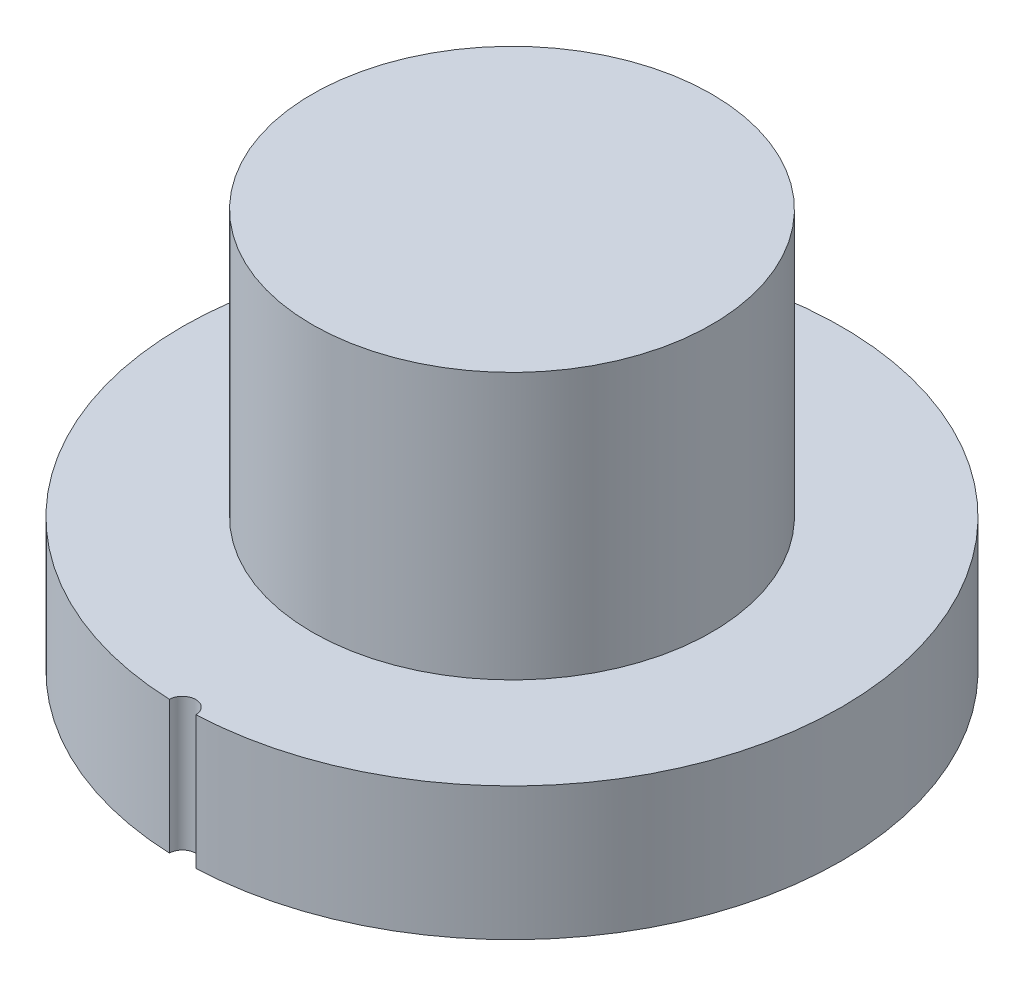
SolidWorks part; units mm, degrees
ref_plane "Front Plane" through (0, 0, 0) normal (0, 0, 1) x (1, 0, 0)
ref_plane "Top Plane" through (0, 0, 0) normal (0, 1, 0) x (1, 0, 0)
ref_plane "Right Plane" through (0, 0, 0) normal (1, 0, 0) x (0, 0, -1)
sketch "Sketch1" plane through (0, 0, 0) normal (0, 1, 0) x (1, 0, 0)
  circle A0 centre (0, 0) radius 12.375
  dimension "D1" = 24.75
extrude "Boss-Extrude1" add sketch "Sketch1" along normal blind 5
sketch "Sketch2" plane through (0, 5, 0) normal (0, 1, 0) x (1, 0, 0)
  circle A0 centre (0, 0) radius 7.5
  dimension "D1" = 15
extrude "Boss-Extrude2" add sketch "Sketch2" along normal blind 10
sketch "Sketch3" plane through (0, 0, 0) normal (0, 1, 0) x (1, 0, 0)
  line L1 (-8, -4) -> (8, -4)
  line L2 (-8, -4) -> (-8, 4)
  line L3 (-8, 4) -> (8, 4)
  line L4 (8, -4) -> (8, 4)
  line L5 (-8, -4) -> (8, 4) construction
  line L6 (-8, 4) -> (8, -4) construction
  point P0 (0, 0)
  dimension "D1" = 16
  dimension "D2" = 8
extrude "Boss-Extrude3" add sketch "Sketch3" along normal blind 10 draft 45 separate body
combine bodies "Combine1" operation type subtract main body 102 bodies to subtract 103
sketch "Sketch4" plane through (0, 0, 0) normal (0, -1, 0) x (1, 0, 0)
  line L0 (-8, 4) -> (8, 4) construction
  line L1 (-1, 4) -> (1, 4)
  line L2 (-1, 4) -> (-1, -4)
  line L3 (-1, -4) -> (1, -4)
  line L4 (1, 4) -> (1, -4)
  line L5 (8, -4) -> (-8, -4) construction
  point P4 (0, 4)
  dimension "D1" = 2
extrude "Boss-Extrude4" add sketch "Sketch4" against normal blind 0.8
sketch "Sketch7" plane through (0, 0, 0) normal (0, 0, 1) x (1, 0, 0)
  line L1 (12.375, 5) -> (-12.375, 5) construction
  circle A0 centre (0, 9.25) radius 1.5
  dimension "D1" = 3
  dimension "D2" = 4.25
extrude "Cut-Extrude3" cut sketch "Sketch7" against normal through all
sketch "Sketch8" plane through (0, 0, 0) normal (0, -1, 0) x (1, 0, 0)
  circle A0 centre (0, 12.375) radius 0.5
  circle A1 centre (0, 0) radius 12.375 construction
  dimension "D1" = 1
extrude "Cut-Extrude4" cut sketch "Sketch8" against normal up to next
